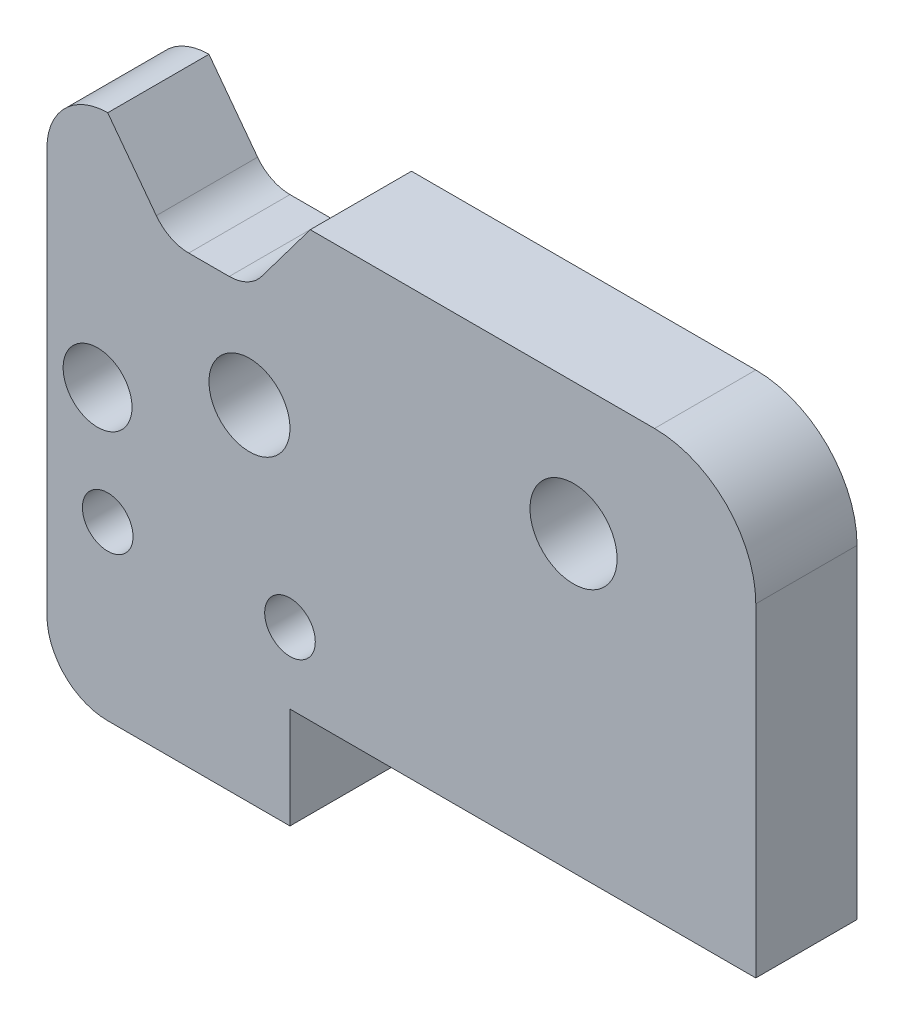
SolidWorks part; units mm, degrees
ref_plane "Front" through (0, 0, 0) normal (0, 0, 1) x (1, 0, 0)
ref_plane "Top" through (0, 0, 0) normal (0, 1, 0) x (1, 0, 0)
ref_plane "Right" through (0, 0, 0) normal (1, 0, 0) x (0, 0, -1)
sketch "Sketch1" plane through (0, 0, 0) normal (0, 0, 1) x (1, 0, 0)
  line L0 (-8, 6.5) -> (-8, -14.5)
  line L1 (-8, -14.5) -> (15, -14.5)
  line L2 (15, -14.5) -> (15, 6.5)
  line L3 (15, 6.5) -> (-8, 6.5)
  dimension "D1" = 8
  dimension "D2" = 15
  dimension "D3" = 6.5
  dimension "D4" = 14.5
extrude "Extrude1" add sketch "Sketch1" along normal blind 5
sketch "Sketch2" plane through (0, 0, 5) normal (0, 0, 1) x (1, 0, 0)
  circle A0 centre (6, 0) radius 2.15
  dimension "D1" = 4.3
  dimension "D2" = 6
extrude "Extrude2" cut sketch "Sketch2" against normal blind 4.5
sketch "Sketch4" plane through (0, -14.5, 0) normal (0, -1, 0) x (1, 0, 0)
  line L0 (-8, 0) -> (15, 0) construction
  line L1 (-8, 5) -> (-8, 0) construction
  line L2 (15, 5) -> (15, 0) construction
  circle A0 centre (-1.4, 2.5) radius 1.25
  circle A1 centre (12, 2.5) radius 1.25
  dimension "D1" = 2.5
  dimension "D2" = 2.5
  dimension "D3" = 2.5
  dimension "D5" = 6.6
  dimension "D6" = 3
  dimension "D4" = 2.5
extrude "Extrude4" cut sketch "Sketch4" against normal blind 8
cosmetic thread "Hole Thread1" parameters "D1"=6, "D2"=3
cosmetic thread "Hole Thread2" parameters "D1"=6, "D2"=3
fillet "Fillet1" radius 5 1 edges at (15, 6.5, 2.5)
sketch "Sketch6" plane through (0, 0, 0) normal (0, 0, -1) x (-1, 0, 0)
  line L0 (8, -14.5) -> (-15, -14.5) construction
  line L1 (8, 6.5) -> (8, -14.5) construction
  circle A0 centre (-4.9, -6.5) radius 2.05
  dimension "D1" = 4.1
  dimension "D3" = 12.9
  dimension "D2" = 8
extrude "Extrude6" cut sketch "Sketch6" against normal blind 4.5
sketch "Sketch9" plane through (0, 0, 0) normal (0, 0, -1) x (-1, 0, 0)
  line L1 (8, 6.5) -> (20, 6.5)
  line L2 (8, 6.5) -> (8, -19.5)
  line L3 (8, -19.5) -> (20, -19.5)
  line L4 (20, 6.5) -> (20, -19.5)
  line L5 (8, -14.5) -> (-15, -14.5) construction
  dimension "D1" = 12
  dimension "D2" = 5
extrude "Extrude9" add sketch "Sketch9" against normal up to surface (5 mm away) up to face at (8.15, 0, 5)
sketch "Sketch11" plane through (0, 0, 5) normal (0, 0, 1) x (1, 0, 0)
  line L0 (-20, -19.5) -> (-20, 6.5) construction
  line L1 (-8, -14.5) -> (15, -14.5) construction
  circle A0 centre (-17.5, -5.5) radius 1.7
  dimension "D1" = 3.4
  dimension "D3" = 9
  dimension "D2" = 2.5
extrude "Extrude11" cut sketch "Sketch11" against normal up to surface (5 mm away) up to face at (2.85, -6.5, 0)
sketch "Sketch10" plane through (0, 0, 5) normal (0, 0, 1) x (1, 0, 0)
  line L0 (10, 6.5) -> (-20, 6.5) construction
  line L1 (-20, -19.5) -> (-20, 6.5) construction
  circle A0 centre (-10, -2.5) radius 2
  dimension "D1" = 4
  dimension "D3" = 10
  dimension "D2" = 9
extrude "Extrude10" cut sketch "Sketch10" against normal blind 4
hole_wizard "M3 Tapped Hole1" positions "3DSketch1" profile "Sketch12" tap size "M3" standard "DIN"
sketch3d "3DSketch1"
  line L0 (-1.4, -6.5, 2.5) -> (-1.4, -14.5, 2.5) construction
  line L1 (12, -6.5, 2.5) -> (12, -14.5, 2.5) construction
  point P0 (-1.4, -14.5, 2.5)
  point P4 (12, -14.5, 2.5)
sketch "Sketch12" plane through (-1.4, -14.5, 2.5) normal (1, 0, 0) x (0, 0, -1)
  line L0 (0, 0) -> (0, 8.7511)
  line L1 (0, 8.7511) -> (1.25, 8)
  line L2 (1.25, 8) -> (1.25, 0)
  line L5 (1.25, 0) -> (0, 0)
  line L10 (0, 8.7511) -> (-1.25, 8) construction
  line L11 (0, -6.35) -> (0, 107.95) construction
  dimension "Tap Drill Dia." = 2.5
  dimension "Tap Drill Depth" = 8
  dimension "Drill Angle" = 118
fillet "Fillet3" radius 3 2 edges at (-20, -19.5, 2.5) (-20, 6.5, 2.5)
sketch "Sketch15" plane through (0, 0, 5) normal (0, 0, 1) x (1, 0, 0)
  line L0 (-14, 2.5) -> (-17, 6.5)
  line L1 (10, 6.5) -> (-17, 6.5) construction
  line L2 (-14, 2.5) -> (-10, 2.5)
  line L3 (-10, 2.5) -> (-7, 6.5)
  line L4 (-17, 6.5) -> (-7, 6.5)
  line L5 (-20, -16.5) -> (-20, 3.5) construction
  dimension "D1" = 6
  dimension "D2" = 4
  dimension "D3" = 10
  dimension "D4" = 4
extrude "Extrude15" cut sketch "Sketch15" against normal up to surface (5 mm away) up to face at (-15.8, -5.5, 0)
fillet "Fillet6" radius 2 2 edges at (-10, 2.5, 2.5) (-14, 2.5, 2.5)
sketch "Sketch16" plane through (0, 0, 0) normal (0, 0, -1) x (-1, 0, 0)
  line L0 (8, -19.5) -> (17, -19.5) construction
  line L1 (20, -16.5) -> (20, 3.5) construction
  circle A0 centre (17, -11) radius 0.75
  circle A1 centre (8, -11) radius 0.75
  dimension "D5" = 1.5
  dimension "D6" = 1.5
  dimension "D1" = 8.5
  dimension "D2" = 8.5
  dimension "D3" = 3
  dimension "D4" = 9
extrude "Extrude16" cut sketch "Sketch16" against normal up to surface (5 mm away) up to face at (-8.3362, -3.2316, 5)
hole_wizard "M3 Tapped Hole2" positions "3DSketch2" profile "Sketch17" tap size "M3" standard "DIN"
sketch3d "3DSketch2"
  line L0 (-8, -11, 5) -> (-8, -11, 0) construction
  line L1 (-17, -11, 5) -> (-17, -11, 0) construction
  point P0 (-8, -11, 0)
  point P4 (-17, -11, 0)
sketch "Sketch17" plane through (-8, -11, 0) normal (1, 0, 0) x (0, 1, 0)
  line L0 (0, 0) -> (0, 8.2511)
  line L1 (0, 8.2511) -> (1.25, 7.5)
  line L2 (1.25, 7.5) -> (1.25, 0)
  line L5 (1.25, 0) -> (0, 0)
  line L10 (0, 8.2511) -> (-1.25, 7.5) construction
  line L11 (0, -6.35) -> (0, 107.95) construction
  dimension "Tap Drill Dia." = 2.5
  dimension "Tap Drill Depth" = 7.5
  dimension "Drill Angle" = 118
cosmetic thread "Hole Thread3" parameters "D1"=5, "D2"=3
cosmetic thread "Hole Thread4" parameters "D1"=5, "D2"=3
